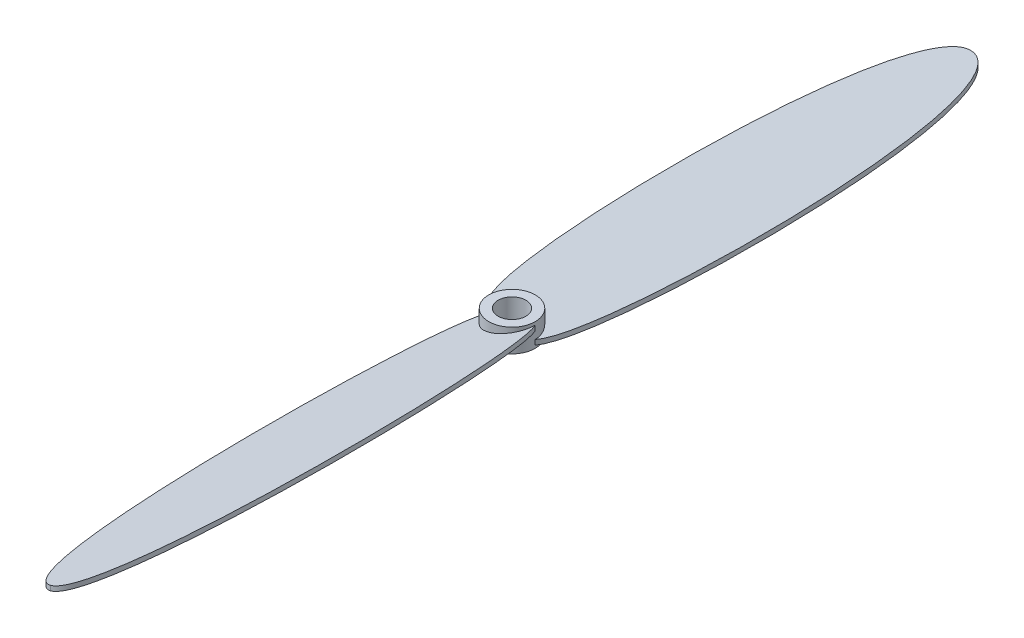
SolidWorks part; units mm, degrees
ref_plane "前基準面" through (0, 0, 0) normal (0, 0, 1) x (1, 0, 0)
ref_plane "上基準面" through (0, 0, 0) normal (0, 1, 0) x (1, 0, 0)
ref_plane "右基準面" through (0, 0, 0) normal (1, 0, 0) x (0, 0, -1)
sketch "草圖1" plane through (0, 0, 0) normal (0, 1, 0) x (1, 0, 0)
  circle A0 centre (0, 0) radius 3
  circle A1 centre (0, 0) radius 5
  dimension "D1" = 6
  dimension "D2" = 10
extrude "填料-伸長1" add sketch "草圖1" along normal blind 5
sketch "草圖9" plane through (0, 5, 0) normal (0, 1, 0) x (1, 0, 0)
  line L0 (0, 0) -> (5, 0) construction
  line L1 (-9.5, 99.5) -> (9.5, 99.5) construction
  line L2 (-9.5, 99.5) -> (-9.5, -99.5) construction
  line L3 (-9.5, -99.5) -> (9.5, -99.5) construction
  line L4 (9.5, 99.5) -> (9.5, -99.5) construction
  line L5 (-9.5, 99.5) -> (9.5, -99.5) construction
  line L6 (-9.5, -99.5) -> (9.5, 99.5) construction
  line L7 (0, 99.5) -> (0, 0) construction
  circle A0 centre (0, 0) radius 5 construction
  spline S0 degree 3 poles (5, 0) (10.5156, 9.3195) (11.321, 99.5) (0, 99.5) knots 0 0 0 0 1 1 1 1
  spline S1 degree 3 poles (-5, 0) (-10.5156, 9.3195) (-11.321, 99.5) (0, 99.5) knots 0 0 0 0 1 1 1 1
  spline S2 degree 3 poles (5, 0) (10.5156, -9.3195) (11.321, -99.5) (0, -99.5) knots 0 0 0 0 1 1 1 1
  spline S3 degree 3 poles (-5, 0) (-10.5156, -9.3195) (-11.321, -99.5) (0, -99.5) knots 0 0 0 0 1 1 1 1
  point P0 (0, 0)
  dimension "D1" = 199
  dimension "D2" = 19
sketch "草圖6" plane through (0, 0, 0) normal (0, 0, 1) x (1, 0, 0)
  line L0 (-5, 3.8397) -> (5, 1.1603) construction
  line L2 (0, 5) -> (0, 0) construction
  line L3 (3, 5) -> (-3, 5) construction
  line L4 (9.6593, -0.0882) -> (-9.6593, 5.0882) construction
  line L5 (9.5298, -0.5712) -> (-9.7887, 4.6052)
  line L6 (9.7887, 0.3948) -> (-9.5298, 5.5712)
  arc A0 (9.5298, -0.5712) -> (9.7887, 0.3948) centre (9.6593, -0.0882) ccw
  arc A1 (-9.5298, 5.5712) -> (-9.7887, 4.6052) centre (-9.6593, 5.0882) ccw
  point P2 (0, 2.5)
  point P12 (0, 2.5)
  dimension "D1" = 75
  dimension "D2" = 1
  dimension "D3" = 20
extrude "填料-伸長7" add sketch "草圖6" against normal blind 100
sketch "草圖7" plane through (0, 0, 0) normal (0, 0, 1) x (1, 0, 0)
  line L0 (9.2834, 4.9875) -> (-9.2834, 0.0125) construction
  line L1 (0, 0) -> (0, 5) construction
  line L2 (3, 5) -> (-3, 5) construction
  line L3 (-9.6593, -0.0882) -> (9.6593, 5.0882) construction
  line L4 (-9.7887, 0.3948) -> (9.5298, 5.5712)
  line L5 (-9.5298, -0.5712) -> (9.7887, 4.6052)
  arc A0 (-9.7887, 0.3948) -> (-9.5298, -0.5712) centre (-9.6593, -0.0882) ccw
  arc A1 (9.7887, 4.6052) -> (9.5298, 5.5712) centre (9.6593, 5.0882) ccw
  point P7 (0, 2.5)
  point P10 (0, 2.5)
  dimension "D1" = 75
  dimension "D2" = 20
  dimension "D3" = 1
extrude "填料-伸長8" add sketch "草圖7" along normal blind 100
sketch "草圖8" plane through (0, 5, 0) normal (0, 1, 0) x (1, 0, 0)
  circle A0 centre (0, 0) radius 3 construction
  circle A1 centre (0, 0) radius 3
extrude "除料-伸長1" cut sketch "草圖8" against normal through all
extrude "除料-伸長2" cut sketch "草圖9" against normal through all and the other way through all flip side to cut
